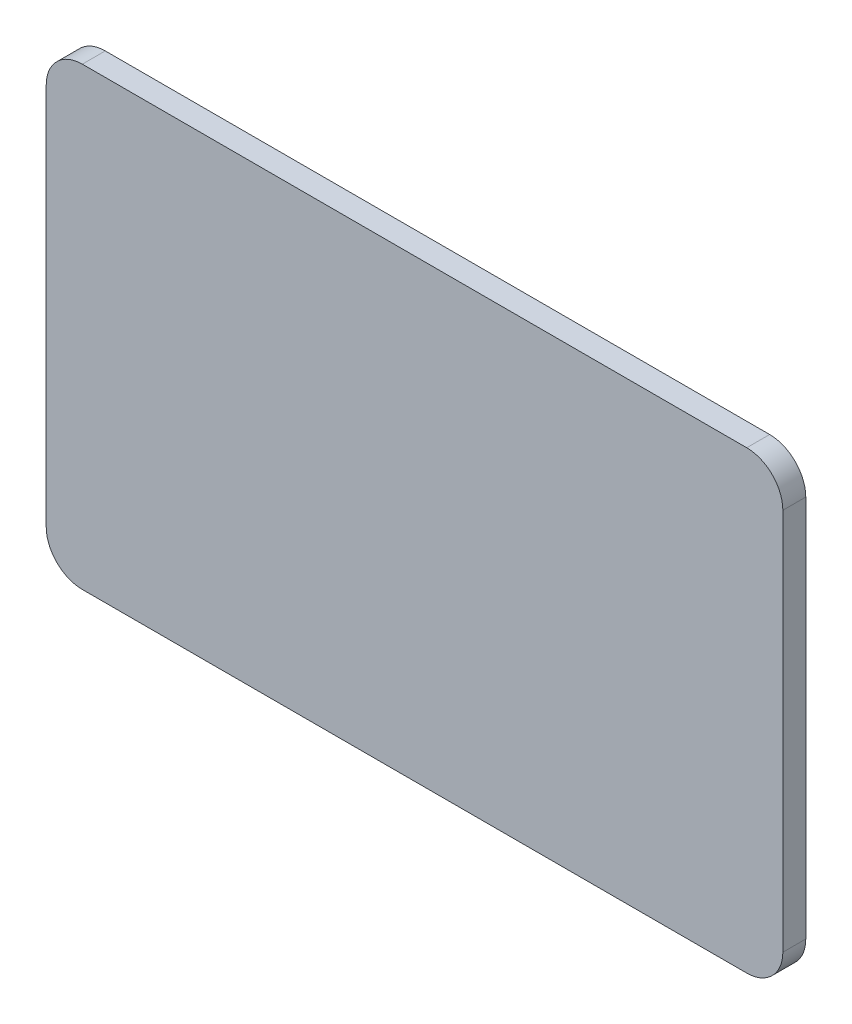
SolidWorks part; units mm, degrees
material "Acrylic (Medium-high impact)"
ref_plane "X-Y Datum" through (0, 0, 0) normal (0, 0, 1) x (1, 0, 0)
ref_plane "X-Z Datum" through (0, 0, 0) normal (0, 1, 0) x (1, 0, 0)
ref_plane "Y-Z Datum" through (0, 0, 0) normal (1, 0, 0) x (0, 0, -1)
sketch "Sketch1" plane through (0, 0, 0) normal (0, 0, 1) x (1, 0, 0)
  line L1 (-51, -31.5) -> (51, -31.5)
  line L2 (-51, -31.5) -> (-51, 31.5)
  line L3 (-51, 31.5) -> (51, 31.5)
  line L4 (51, -31.5) -> (51, 31.5)
  line L5 (-51, -31.5) -> (51, 31.5) construction
  line L6 (-51, 31.5) -> (51, -31.5) construction
  point P0 (0, 0)
  dimension "D1" = 63
  dimension "D2" = 102
extrude "Boss-Extrude1" add sketch "Sketch1" along normal blind 3.175
fillet "Fillet1" radius 5 4 edges at (-51, -31.5, 1.5875) (-51, 31.5, 1.5875) (51, -31.5, 1.5875) (51, 31.5, 1.5875)
